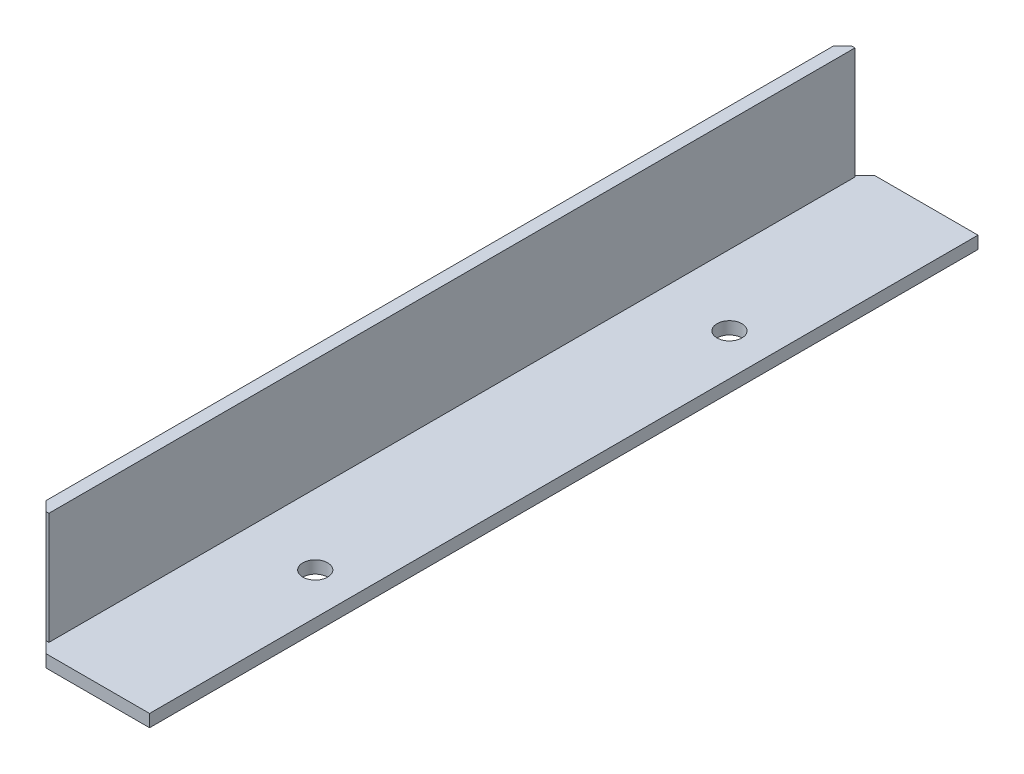
SolidWorks part; units mm, degrees
ref_plane "Plan de face" through (0, 0, 0) normal (0, 0, 1) x (1, 0, 0)
ref_plane "Plan de dessus" through (0, 0, 0) normal (0, 1, 0) x (1, 0, 0)
ref_plane "Plan de droite" through (0, 0, 0) normal (1, 0, 0) x (0, 0, -1)
sketch "Esquisse1" plane through (0, 0, 0) normal (0, 0, 1) x (1, 0, 0)
  line L1 (0, 0) -> (1.5, 0)
  line L2 (0, 0) -> (0, 15)
  line L3 (0, 15) -> (1.5, 15)
  line L4 (1.5, 1.5) -> (1.5, 15)
  line L5 (1.5, 0) -> (15, 0)
  line L7 (1.5, 1.5) -> (15, 1.5)
  line L8 (15, 0) -> (15, 1.5)
  dimension "D1" = 1.5
  dimension "D2" = 15
  dimension "D3" = 1.5
  dimension "D4" = 13.5
  dimension "D5" = 13.5
extrude "Extrusion1" add sketch "Esquisse1" along normal blind 100
sketch "Esquisse2" plane through (0, 0, 0) normal (0, -1, 0) x (1, 0, 0)
  line L0 (0, 100) -> (15, 100) construction
  line L1 (15, 100) -> (15, 0) construction
  circle A0 centre (10, 75) radius 1.5
  point P2 (7.5, 100)
  dimension "D1" = 3
  dimension "D2" = 25
  dimension "D3" = 5
extrude "Extrusion2" cut sketch "Esquisse2" against normal blind 100
pattern_linear "Répétition linéaire1" count 2 spacing 50 along (0, 0, -1) of "Extrusion2"
chamfer "Chanfrein1" distance 2.5 angle 45 2 edges at (0, 7.5, 100) (0, 7.5, 0)
chamfer "Chanfrein3" distance 0.5 angle 45 2 edges at (1.5, 8.25, 99) (1.5, 8.25, 1)
